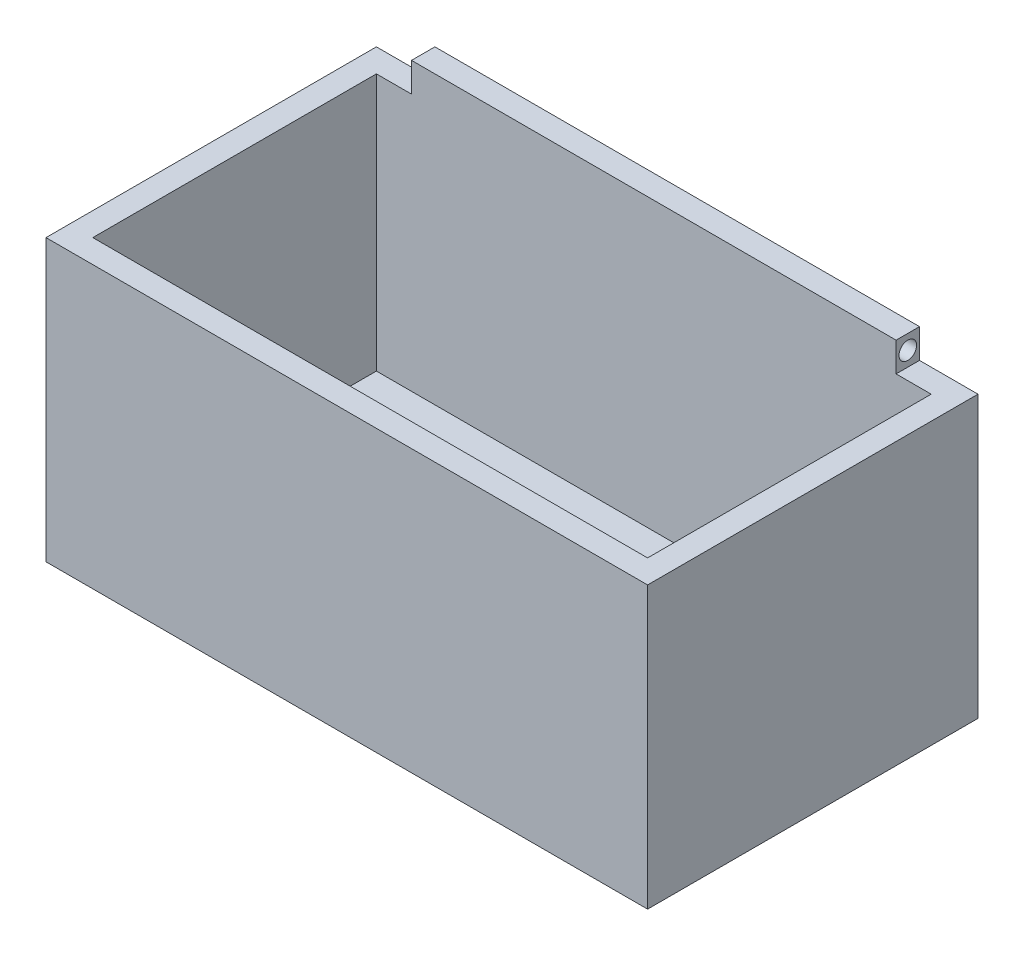
SolidWorks part; units mm, degrees
ref_plane "Front Plane" through (0, 0, 0) normal (0, 0, 1) x (1, 0, 0)
ref_plane "Top Plane" through (0, 0, 0) normal (0, 1, 0) x (1, 0, 0)
ref_plane "Right Plane" through (0, 0, 0) normal (1, 0, 0) x (0, 0, -1)
sketch "Sketch1" plane through (0, 0, 0) normal (0, 0, 1) x (1, 0, 0)
  line L1 (-326.517, -152.4) -> (326.517, -152.4)
  line L2 (-326.517, -152.4) -> (-326.517, 152.4)
  line L3 (-326.517, 152.4) -> (326.517, 152.4)
  line L4 (326.517, -152.4) -> (326.517, 152.4)
  line L5 (-326.517, -152.4) -> (326.517, 152.4) construction
  line L6 (-326.517, 152.4) -> (326.517, -152.4) construction
  point P0 (0, 0)
  dimension "D1" = 653.034
  dimension "D2" = 304.8
extrude "Boss-Extrude1" add sketch "Sketch1" along normal blind 358.648
shell "Shell1" thickness 25.4
sketch "Sketch2" plane through (0, 152.4, 0) normal (0, 1, 0) x (1, 0, 0)
  line L0 (-263.017, 0) -> (263.017, 0)
  line L1 (326.517, 0) -> (-326.517, 0) construction
  line L2 (-263.017, 0) -> (-263.017, -25.4)
  line L3 (-301.117, -25.4) -> (301.117, -25.4) construction
  line L4 (-263.017, -25.4) -> (263.017, -25.4)
  line L5 (301.117, -25.4) -> (-301.117, -25.4) construction
  line L6 (263.017, -25.4) -> (263.017, 0)
  point P6 (0, 0)
  dimension "D1" = 526.034
extrude "Boss-Extrude2" add sketch "Sketch2" along normal blind 31.75
sketch "Sketch4" plane through (263.017, 0, 0) normal (1, 0, 0) x (0, 0, -1)
  circle A0 centre (-12.7, 180.975) radius 9.525
  dimension "D1" = 19.05
ref_plane "Plane2" through (0, 0, 0) normal (1, 0, 0) x (0, 0, -1)
sketch "Sketch5" plane through (263.017, 0, 0) normal (1, 0, 0) x (0, 0, -1)
  circle A0 centre (-12.7, 168.275) radius 9.525
  dimension "D1" = 19.05
extrude "Cut-Extrude2" cut sketch "Sketch5" against normal blind 25.4
mirror "Mirror2" about plane through (0, 0, 0) normal (1, 0, 0) of "Cut-Extrude2"
